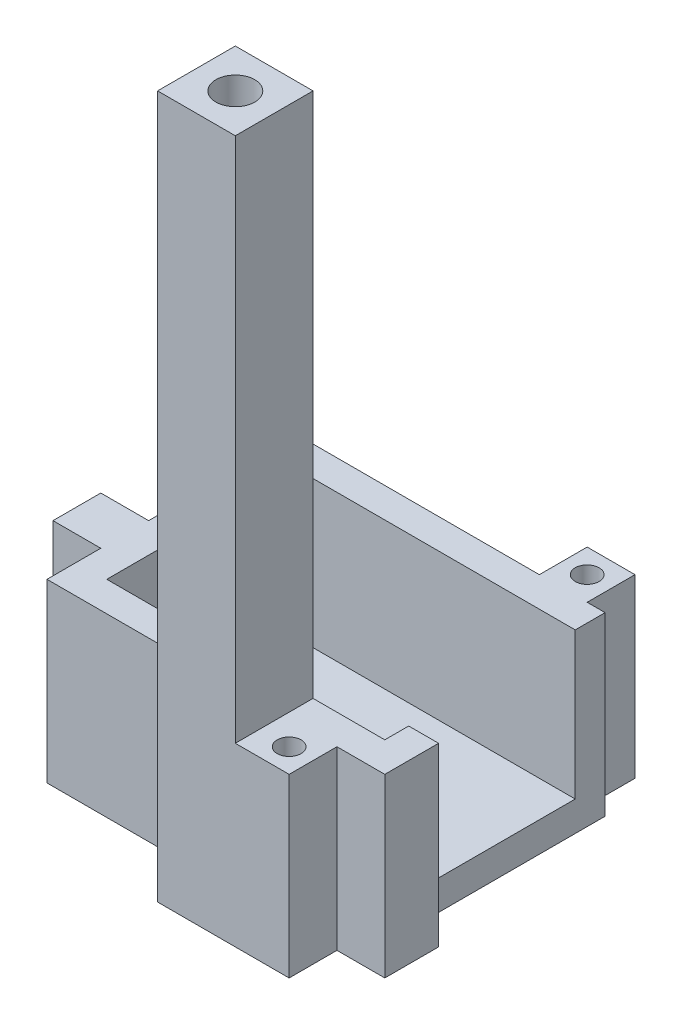
SolidWorks part; units mm, degrees
ref_plane "Front Plane" through (0, 0, 0) normal (0, 0, 1) x (1, 0, 0)
ref_plane "Top Plane" through (0, 0, 0) normal (0, 1, 0) x (1, 0, 0)
ref_plane "Right Plane" through (0, 0, 0) normal (1, 0, 0) x (0, 0, -1)
sketch "Sketch1" plane through (0, 0, 0) normal (0, 1, 0) x (1, 0, 0)
  line L17 (0, 0) -> (51.5, 0)
  line L18 (51.5, 0) -> (51.5, -5)
  line L19 (51.5, -5) -> (5, -5)
  line L20 (5, -5) -> (5, -36.85)
  line L21 (5, -36.85) -> (51.5, -36.85)
  line L22 (51.5, -36.85) -> (51.5, -32.85)
  line L23 (51.5, -32.85) -> (56.5, -32.85)
  line L24 (56.5, -32.85) -> (56.5, -41.85)
  line L25 (56.5, -41.85) -> (0, -41.85)
  line L26 (0, -41.85) -> (0, 0)
  dimension "D1" = 31.85
  dimension "D2" = 5
  dimension "D3" = 5
  dimension "D4" = 5
  dimension "D5" = 5
  dimension "D6" = 51.5
  dimension "D7" = 56.5
  dimension "D8" = 4
extrude "Boss-Extrude1" add sketch "Sketch1" along normal blind 24.5
sketch "Sketch2" plane through (0, 0, 0) normal (0, -1, 0) x (1, 0, 0)
  line L1 (0, 41.85) -> (103, 41.85)
  line L2 (0, 41.85) -> (0, 0)
  line L3 (0, 0) -> (103, 0)
  line L4 (103, 41.85) -> (103, 0)
  dimension "D1" = 103
extrude "Boss-Extrude2" add sketch "Sketch2" along normal blind 5
sketch "Sketch3" plane through (0, 0, 0) normal (0, 1, 0) x (1, 0, 0)
  line L0 (56.5, -32.85) -> (51.5, -32.85) construction
  line L1 (51.5, -5) -> (98, -5)
  line L2 (51.5, -5) -> (51.5, -32.85)
  line L3 (51.5, -32.85) -> (98, -32.85)
  line L4 (98, -5) -> (98, -32.85)
  line L6 (103, 0) -> (103, -41.85) construction
  dimension "D1" = 0
  dimension "D2" = 5
extrude "Cut-Extrude1" cut sketch "Sketch3" against normal blind 26
sketch "Sketch4" plane through (0, 0, 41.85) normal (0, 0, 1) x (1, 0, 0)
  line L1 (0, -5) -> (8, -5)
  line L2 (0, -5) -> (0, -2)
  line L3 (0, -2) -> (8, -2)
  line L4 (8, -5) -> (8, -2)
  dimension "D1" = 3
  dimension "D2" = 8
sketch "Sketch7" plane through (0, 0, 41.85) normal (0, 0, 1) x (1, 0, 0)
  line L1 (0, -2) -> (8, -2)
  line L2 (0, -2) -> (0, -5)
  line L3 (0, -5) -> (8, -5)
  line L4 (8, -2) -> (8, -5)
extrude "Boss-Extrude3" add sketch "Sketch7" along normal blind 8
sketch "Sketch8" plane through (0, -2, 0) normal (0, 1, 0) x (1, 0, 0)
  line L0 (8, -49.85) -> (8, -41.85) construction
  line L1 (0, -41.85) -> (8, -41.85) construction
  circle A0 centre (4, -45.85) radius 2.5
  dimension "D1" = 5
  dimension "D2" = 4
  dimension "D3" = 4
extrude "Cut-Extrude2" cut sketch "Sketch8" against normal blind 8
sketch "Sketch9" plane through (0, 0, 0) normal (0, 0, -1) x (-1, 0, 0)
  line L1 (-103, -5) -> (-95, -5)
  line L2 (-103, -5) -> (-103, -2)
  line L3 (-103, -2) -> (-95, -2)
  line L4 (-95, -5) -> (-95, -2)
  dimension "D1" = 3
  dimension "D2" = 8
extrude "Boss-Extrude4" add sketch "Sketch9" along normal blind 8
sketch "Sketch10" plane through (0, -2, 0) normal (0, 1, 0) x (1, 0, 0)
  line L0 (103, 8) -> (103, 0) construction
  line L1 (95, 8) -> (103, 8) construction
  circle A0 centre (99, 3.9967) radius 2.5
  dimension "D1" = 5
  dimension "D2" = 4
  dimension "D3" = 4.0033
extrude "Cut-Extrude3" cut sketch "Sketch10" against normal blind 8
sketch "Sketch12" plane through (0, 0, 0) normal (0, 1, 0) x (1, 0, 0)
  line L0 (98, -5) -> (51.5, -5) construction
  line L1 (95, -5) -> (83.5, -5)
  line L2 (95, -5) -> (95, 0)
  line L3 (95, 0) -> (83.5, 0)
  line L4 (83.5, -5) -> (83.5, 0)
  line L5 (51.5, 0) -> (103, 0) construction
  line L6 (95, 8) -> (95, 0) construction
  line L7 (51.5, -5) -> (51.5, 0) construction
  dimension "D1" = 0
  dimension "D2" = 32
extrude "Cut-Extrude4" cut sketch "Sketch12" against normal blind 8
sketch "Sketch14" plane through (0, 0, 0) normal (0, 0, -1) x (-1, 0, 0)
  line L1 (-83.5, -5) -> (-75.5, -5)
  line L2 (-83.5, -5) -> (-83.5, -2)
  line L3 (-83.5, -2) -> (-75.5, -2)
  line L4 (-75.5, -5) -> (-75.5, -2)
  dimension "D1" = 8
  dimension "D2" = 3
extrude "Boss-Extrude5" add sketch "Sketch14" along normal blind 8
sketch "Sketch15" plane through (0, -2, 0) normal (0, 1, 0) x (1, 0, 0)
  line L0 (75.5, 8) -> (83.5, 8) construction
  line L1 (83.5, 8) -> (83.5, 0) construction
  circle A0 centre (79.5, 4) radius 2.5
  dimension "D1" = 5
  dimension "D2" = 4
  dimension "D3" = 4
extrude "Cut-Extrude5" cut sketch "Sketch15" against normal blind 8
sketch "Sketch16" plane through (0, 0, 0) normal (0, 0, -1) x (-1, 0, 0)
  line L12 (-51.5, 24.5) -> (0, 24.5) construction
  line L17 (-48.5, 24.5) -> (-40.5, 24.5)
  line L18 (-48.5, 24.5) -> (-48.5, -5)
  line L19 (-48.5, -5) -> (-40.5, -5)
  line L20 (-40.5, 24.5) -> (-40.5, -5)
  line L21 (0, -5) -> (-75.5, -5) construction
  line L22 (-51.5, 24.5) -> (-51.5, 0) construction
  dimension "D1" = 8
  dimension "D2" = 3
extrude "Boss-Extrude6" add sketch "Sketch16" along normal blind 8
sketch "Sketch17" plane through (0, 0, 41.85) normal (0, 0, 1) x (1, 0, 0)
  line L0 (0, 24.5) -> (56.5, 24.5) construction
  line L1 (48.5, 24.5) -> (34.5, 24.5)
  line L2 (48.5, 24.5) -> (48.5, -5)
  line L3 (48.5, -5) -> (34.5, -5)
  line L4 (34.5, 24.5) -> (34.5, -5)
  line L5 (103, -5) -> (8, -5) construction
  line L6 (56.5, 24.5) -> (56.5, 0) construction
  dimension "D1" = 8
  dimension "D2" = 14
extrude "Boss-Extrude7" add sketch "Sketch17" along normal blind 8
sketch "Sketch18" plane through (0, 24.5, 0) normal (0, 1, 0) x (1, 0, 0)
  line L0 (48.5, 8) -> (48.5, 0) construction
  line L2 (40.5, 8) -> (48.5, 8) construction
  line L3 (48.5, -49.85) -> (48.5, -41.85) construction
  line L4 (48.5, -49.85) -> (34.5, -49.85) construction
  circle A0 centre (44.5, 4) radius 2
  circle A1 centre (44.5, -45.85) radius 2
  dimension "D5" = 4
  dimension "D6" = 4
  dimension "D1" = 4
  dimension "D2" = 4
  dimension "D3" = 4
  dimension "D4" = 4
extrude "Cut-Extrude6" cut sketch "Sketch18" against normal blind 10
sketch "Sketch19" plane through (34.5, 0, 0) normal (-1, 0, 0) x (0, 0, 1)
  line L1 (41.85, 24.5) -> (49.85, 24.5)
  line L2 (41.85, 24.5) -> (41.85, -5)
  line L3 (41.85, -5) -> (49.85, -5)
  line L4 (49.85, 24.5) -> (49.85, -5)
extrude "Boss-Extrude8" add sketch "Sketch19" along normal blind 8
sketch "Sketch20" plane through (0, 24.5, 0) normal (0, 1, 0) x (1, 0, 0)
  line L2 (51.5, -36.85) -> (5, -36.85) construction
  line L7 (26.5, -49.85) -> (39.5, -49.85)
  line L8 (26.5, -49.85) -> (26.5, -36.85)
  line L9 (26.5, -36.85) -> (39.5, -36.85)
  line L10 (39.5, -49.85) -> (39.5, -36.85)
  dimension "D1" = 13
extrude "Boss-Extrude9" add sketch "Sketch20" along normal blind 88
sketch "Sketch22" plane through (0, 0, 0) normal (0, 1, 0) x (1, 0, 0)
  line L1 (103, 8) -> (51.5, 8)
  line L2 (103, 8) -> (103, -32.85)
  line L3 (103, -32.85) -> (51.5, -32.85)
  line L4 (51.5, 8) -> (51.5, -32.85)
  line L5 (103, -32.85) -> (56.5, -32.85)
  line L6 (103, -32.85) -> (103, -41.85)
  line L7 (103, -41.85) -> (56.5, -41.85)
  line L8 (56.5, -32.85) -> (56.5, -41.85)
  line M1 (103, 0) -> (95, 0)
  line M2 (95, 0) -> (95, -5)
  line M3 (95, -5) -> (98, -5)
  line M4 (98, -5) -> (98, -32.85)
  line M5 (98, -32.85) -> (56.5, -32.85)
  line M6 (56.5, -32.85) -> (56.5, -41.85)
  line M7 (56.5, -41.85) -> (103, -41.85)
  line M8 (103, -41.85) -> (103, 0)
extrude "Cut-Extrude8" cut sketch "Sketch22" against normal blind 48 contours L1 L4 L3 L2 M5 M4 M3 M2 M1 | L3 M8 M5 M6 M7 | L3 M8 M1 M2 M3 M4
sketch "Sketch23" plane through (0, -5, 0) normal (0, -1, 0) x (1, 0, 0)
  line L1 (48.5, 0) -> (40.5, 0)
  line L2 (48.5, 0) -> (48.5, -8)
  line L3 (48.5, -8) -> (40.5, -8)
  line L4 (40.5, 0) -> (40.5, -8)
  circle A0 centre (44.5, -4) radius 2.5
  dimension "D1" = 5
  dimension "D2" = 4
  dimension "D3" = 4
extrude "Cut-Extrude9" cut sketch "Sketch23" against normal blind 10 contours A0
sketch "Sketch26" plane through (0, 112.5, 0) normal (0, 1, 0) x (1, 0, 0)
  line L0 (39.5, -49.85) -> (39.5, -36.85) construction
  line L1 (39.5, -36.85) -> (26.5, -36.85) construction
  circle A0 centre (33, -43.35) radius 3.25
  dimension "D1" = 6.5
  dimension "D2" = 6.5
  dimension "D3" = 6.5
extrude "Cut-Extrude11" cut sketch "Sketch26" against normal up to surface (117.5 mm away) up to face at (44.5, -5, -6.5)
sketch "Sketch25" plane through (0, 0, 49.85) normal (0, 0, 1) x (1, 0, 0)
  line L1 (0, -5) -> (8, -5)
  line L2 (0, -5) -> (0, -2)
  line L3 (0, -2) -> (8, -2)
  line L4 (8, -5) -> (8, -2)
extrude "Cut-Extrude10" cut sketch "Sketch25" against normal blind 8
sketch "Sketch27" plane through (0, 0, 0) normal (-1, 0, 0) x (0, 0, 1)
  line L0 (0, 24.5) -> (41.85, 24.5) construction
  line L1 (32.85, 24.5) -> (24.85, 24.5)
  line L2 (32.85, 24.5) -> (32.85, -5)
  line L3 (32.85, -5) -> (24.85, -5)
  line L4 (24.85, 24.5) -> (24.85, -5)
  line L5 (41.85, -5) -> (0, -5) construction
  line L6 (36.85, 112.5) -> (36.85, 24.5) construction
  dimension "D1" = 8
  dimension "D2" = 4
extrude "Boss-Extrude11" add sketch "Sketch27" along normal blind 8
sketch "Sketch28" plane through (0, -5, 0) normal (0, -1, 0) x (1, 0, 0)
  line L0 (-8, 24.85) -> (-8, 32.85) construction
  line L1 (-8, 32.85) -> (0, 32.85) construction
  circle A1 centre (-4, 28.85) radius 2.5
  dimension "D1" = 4
  dimension "D3" = 5
  dimension "D2" = 4
extrude "Cut-Extrude12" cut sketch "Sketch28" against normal blind 15
